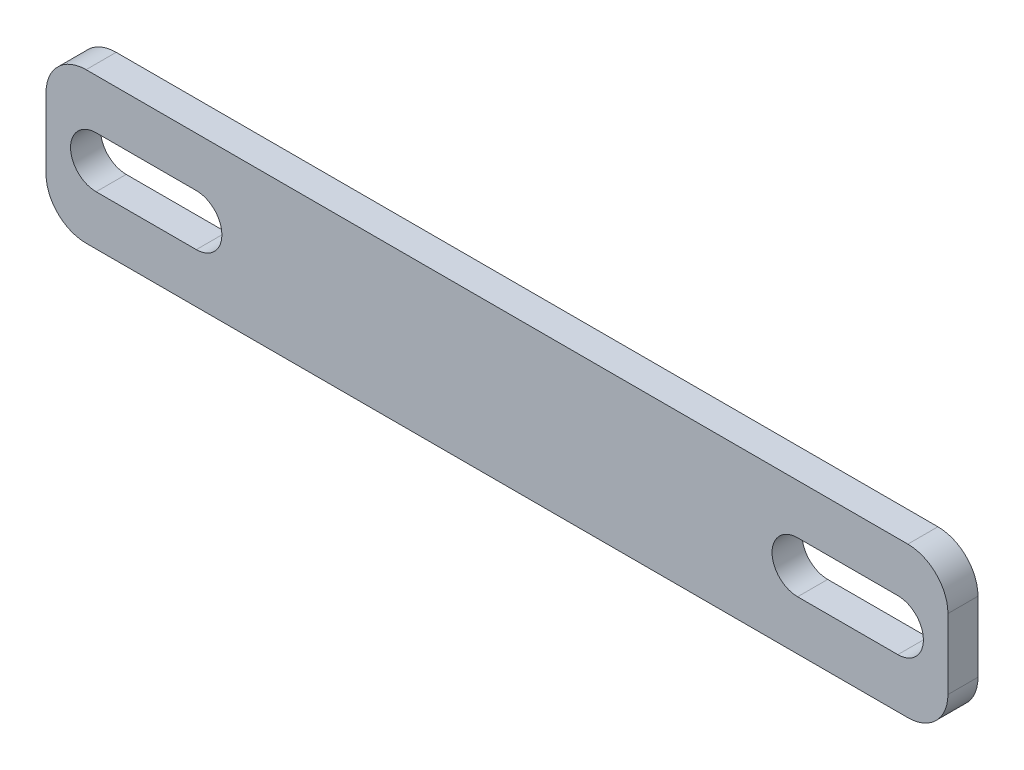
SolidWorks part; units mm, degrees
ref_plane "Ebene vorne" through (0, 0, 0) normal (0, 0, 1) x (1, 0, 0)
ref_plane "Ebene oben" through (0, 0, 0) normal (0, 1, 0) x (1, 0, 0)
ref_plane "Ebene rechts" through (0, 0, 0) normal (1, 0, 0) x (0, 0, -1)
sketch "Model" plane through (0, 0, 0) normal (0, 0, 1) x (1, 0, 0)
  line L0 (4, 0) -> (86, 0)
  line L1 (90, 4) -> (90, 11)
  line L2 (86, 15) -> (4, 15)
  line L3 (0, 11) -> (0, 4)
  line L4 (5, 4.95) -> (15, 4.95)
  line L5 (15, 10.05) -> (5, 10.05)
  line L6 (75, 4.95) -> (85, 4.95)
  line L7 (85, 10.05) -> (75, 10.05)
  arc A0 (86, 0) -> (90, 4) centre (86, 4) ccw
  arc A1 (90, 11) -> (86, 15) centre (86, 11) ccw
  arc A2 (4, 15) -> (0, 11) centre (4, 11) ccw
  arc A3 (0, 4) -> (4, 0) centre (4, 4) ccw
  arc A4 (15, 4.95) -> (15, 10.05) centre (15, 7.5) ccw
  arc A5 (5, 10.05) -> (5, 4.95) centre (5, 7.5) ccw
  arc A6 (85, 4.95) -> (85, 10.05) centre (85, 7.5) ccw
  arc A7 (75, 10.05) -> (75, 4.95) centre (75, 7.5) ccw
extrude "Aufsatz-Linear austragen1" add sketch "Model" along normal blind 3
